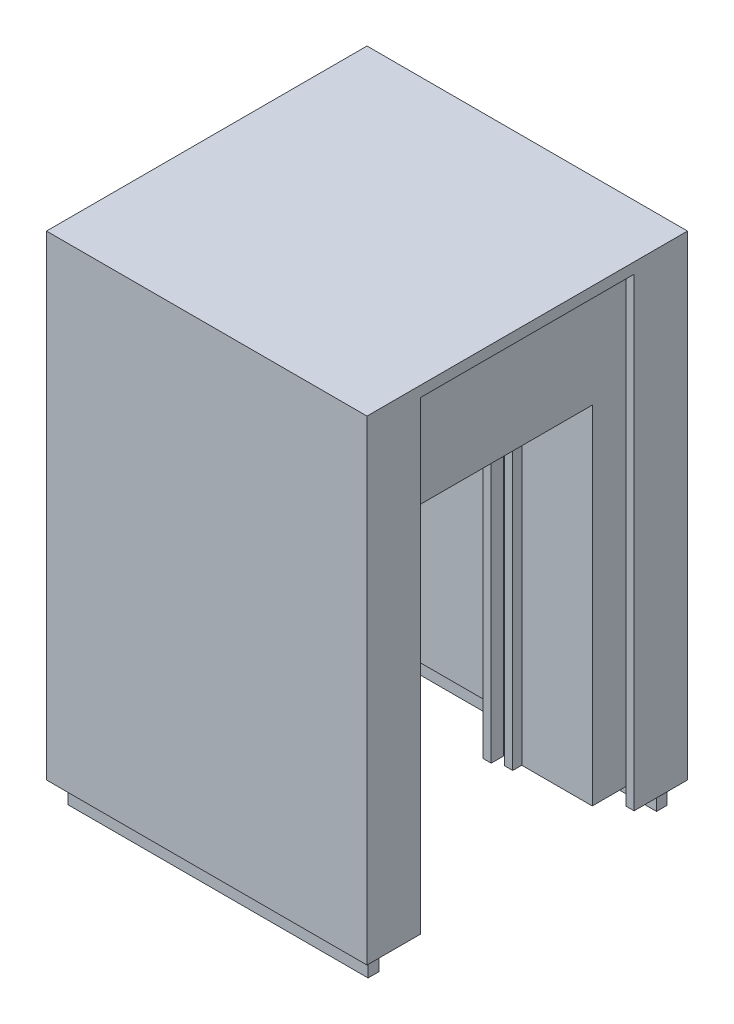
SolidWorks part; units mm, degrees
ref_plane "Front Plane" through (0, 0, 0) normal (0, 0, 1) x (1, 0, 0)
ref_plane "Top Plane" through (0, 0, 0) normal (0, 1, 0) x (1, 0, 0)
ref_plane "Right Plane" through (0, 0, 0) normal (1, 0, 0) x (0, 0, -1)
sketch "Sketch1" plane through (0, 0, 0) normal (0, 1, 0) x (1, 0, 0)
  line L0 (30, 20) -> (28.5, 20)
  line L1 (-30, -30) -> (30, -30)
  line L2 (-30, -30) -> (-30, 30)
  line L3 (-30, 30) -> (30, 30)
  line L4 (30, -30) -> (30, -20)
  line L5 (-30, -30) -> (30, 30) construction
  line L6 (-30, 30) -> (30, -30) construction
  line L7 (28.5, 20) -> (28.5, 23.5)
  line L8 (28.5, 23.5) -> (25.3, 23.5)
  line L9 (25.3, 23.5) -> (25.3, 16.8714)
  line L10 (25.3, 16.8714) -> (12.1, 16.8714)
  line L11 (12.1, 16.8714) -> (12.1, 15.1818)
  line L12 (12.1, 15.1818) -> (10.6, 15.1818)
  line L13 (10.6, 15.1818) -> (10.6, 16.6857)
  line L14 (10.6, 16.6857) -> (8.9, 16.6857)
  line L15 (8.9, 16.6857) -> (8.9, 14.3462)
  line L16 (8.9, 14.3462) -> (7.4, 14.3462)
  line L17 (7.4, 14.3462) -> (7.4, 24)
  line L18 (22.3, 24) -> (22.3, 19.0293)
  line L19 (22.3, 19.0293) -> (9.4, 19.0293)
  line L20 (9.4, 19.0293) -> (9.4, 24)
  line L21 (9.4, 24) -> (22.3, 24)
  line L22 (7.4, 24) -> (-24, 24)
  line L23 (-24, 24) -> (-24, -24)
  line L24 (-27.7482, 0) -> (34.8331, 0) construction
  line L25 (7.95, 22.3434) -> (7.95, -37.931) construction
  line L26 (7.4, -24) -> (-24, -24)
  line L27 (7.4, -14.3462) -> (7.4, -24)
  line L28 (8.9, -14.3462) -> (7.4, -14.3462)
  line L29 (8.9, -16.6857) -> (8.9, -14.3462)
  line L30 (10.6, -16.6857) -> (8.9, -16.6857)
  line L31 (12.1, -15.1818) -> (10.6, -15.1818)
  line L32 (10.6, -15.1818) -> (10.6, -16.6857)
  line L33 (12.1, -16.8714) -> (12.1, -15.1818)
  line L34 (9.4, -19.0293) -> (9.4, -24)
  line L35 (9.4, -24) -> (22.3, -24)
  line L36 (22.3, -24) -> (22.3, -19.0293)
  line L37 (22.3, -19.0293) -> (9.4, -19.0293)
  line L38 (25.3, -16.8714) -> (12.1, -16.8714)
  line L39 (25.3, -23.5) -> (25.3, -16.8714)
  line L40 (28.5, -23.5) -> (25.3, -23.5)
  line L41 (28.5, -20) -> (28.5, -23.5)
  line L42 (30, -20) -> (28.5, -20)
  line L43 (30, 20) -> (30, 30)
  line L44 (30, 28) -> (-30, 28) construction
  point P0 (0, 0)
  point P30 (-24, 0)
  dimension "D1" = 60
  dimension "D2" = 60
  dimension "D3" = 1.5
  dimension "D4" = 3.2
  dimension "D5" = 1.7
  dimension "D6" = 13.2
  dimension "D7" = 1.5
  dimension "D8" = 1.5
  dimension "D9" = 10
  dimension "D10" = 2
  dimension "D11" = 3
  dimension "D12" = 6
  dimension "D13" = 6
  dimension "D14" = 33.3714
  dimension "D15" = 2
  dimension "D16" = 47
extrude "Boss-Extrude1" add sketch "Sketch1" against normal blind 87 and the other way blind 0.0001 contours L1 L4 L42 L41 L40 L39 L38 L33 L31 L32 L30 L29 L28 L27 L26 L23 L22 L17 L16 L15 L14 L13 L12 L11 L10 L9 L8 L7 L0 L43 L3 L2
sketch "Sketch4" plane through (0, 0.0001, 0) normal (0, 1, 0) x (1, 0, 0)
  line L1 (-30, 30) -> (30, 30)
  line L2 (-30, 30) -> (-30, -30)
  line L3 (-30, -30) -> (30, -30)
  line L4 (30, 30) -> (30, -30)
extrude "Boss-Extrude2" add sketch "Sketch4" along normal blind 2
sketch "Sketch6" plane through (0, -87, 0) normal (0, -1, 0) x (1, 0, 0)
  line L0 (28.2, -28) -> (-28, -28)
  line L5 (-28, -28) -> (-28, 28)
  line L6 (-28, 28) -> (28.2, 28)
  line L7 (28.2, 26) -> (28.2, 28)
  line L17 (-26, 26) -> (28.2, 26)
  line L18 (-26, -26) -> (-26, 26)
  line L19 (28.2, -26) -> (-26, -26)
  line L20 (28.2, -28) -> (28.2, -26)
  line L21 (-30, -30) -> (30, -30) construction
  line L23 (30, -20) -> (30, -30) construction
  line L24 (-30, 30) -> (-30, -30) construction
  line L25 (-30, 30) -> (30, 30) construction
  line L26 (30, 30) -> (30, 20) construction
  dimension "D1" = 2
  dimension "D2" = 1.8
  dimension "D3" = 2
  dimension "D4" = 2
  dimension "D5" = 2
  dimension "D6" = 2
  dimension "D7" = 1.8
  dimension "D8" = 2
sketch "Sketch10" plane through (0, 0, 16.8714) normal (0, 0, -1) x (-1, 0, 0)
  line L0 (-12.1, 0.0001) -> (-12.1, -22)
  line L1 (-12.1, 0.0001) -> (-12.1, -87) construction
  line L2 (-25.3, -87) -> (-12.1, -87) construction
  line L3 (-12.1, -22) -> (-7.4533, -22)
  line L4 (-7.4533, -22) -> (-7.4533, 0.0001)
  line L5 (-7.4533, 0.0001) -> (-12.1, 0.0001)
  dimension "D1" = 65
extrude "Boss-Extrude6" add sketch "Sketch10" along normal blind 4
sketch "Sketch12" plane through (0, 0, 16.8714) normal (0, 0, -1) x (-1, 0, 0)
  line L2 (-20.3, -22) -> (-25.3, -22)
  line L3 (-25.3, 0.0001) -> (-25.3, -87) construction
  line L4 (-25.3, -22) -> (-25.3, 0.0001)
  line L5 (-25.3, 0.0001) -> (-20.3, 0.0001)
  line L7 (-25.3, -87) -> (-12.1, -87) construction
  line L9 (-20.3, -22) -> (-20.3, 0.0001)
  dimension "D1" = 65
  dimension "D2" = 5
extrude "Boss-Extrude7" add sketch "Sketch12" along direction (0, 0, 1) on the side of the normal up to surface (33.7429 mm away)
extrude "Boss-Extrude8" add sketch "Sketch6" along normal blind 4
sketch "Sketch13" plane through (-30, 0, 0) normal (-1, 0, 0) x (0, 0, 1)
  line L0 (30, 2.0001) -> (30, -87) construction
  line L1 (-30, 2.0001) -> (30, 2.0001) construction
  circle A0 centre (14, -7.9999) radius 6.25
  dimension "D1" = 12.5
  dimension "D3" = 10
  dimension "D2" = 16
extrude "Cut-Extrude1" cut sketch "Sketch13" against normal blind 10
sketch "Sketch14" plane through (0, 0, -30) normal (0, 0, -1) x (-1, 0, 0)
  line L0 (-30, 2.0001) -> (30, 2.0001) construction
  line L1 (30, 2.0001) -> (30, -87) construction
  circle A0 centre (15, -12.9999) radius 8.5
  circle A1 centre (15, -36.9999) radius 8.5
  dimension "D1" = 17
  dimension "D2" = 15
  dimension "D3" = 15
  dimension "D4" = 17
  dimension "D5" = 24
  dimension "D6" = 15
extrude "Cut-Extrude2" cut sketch "Sketch14" against normal blind 10 contours A0 | A1
